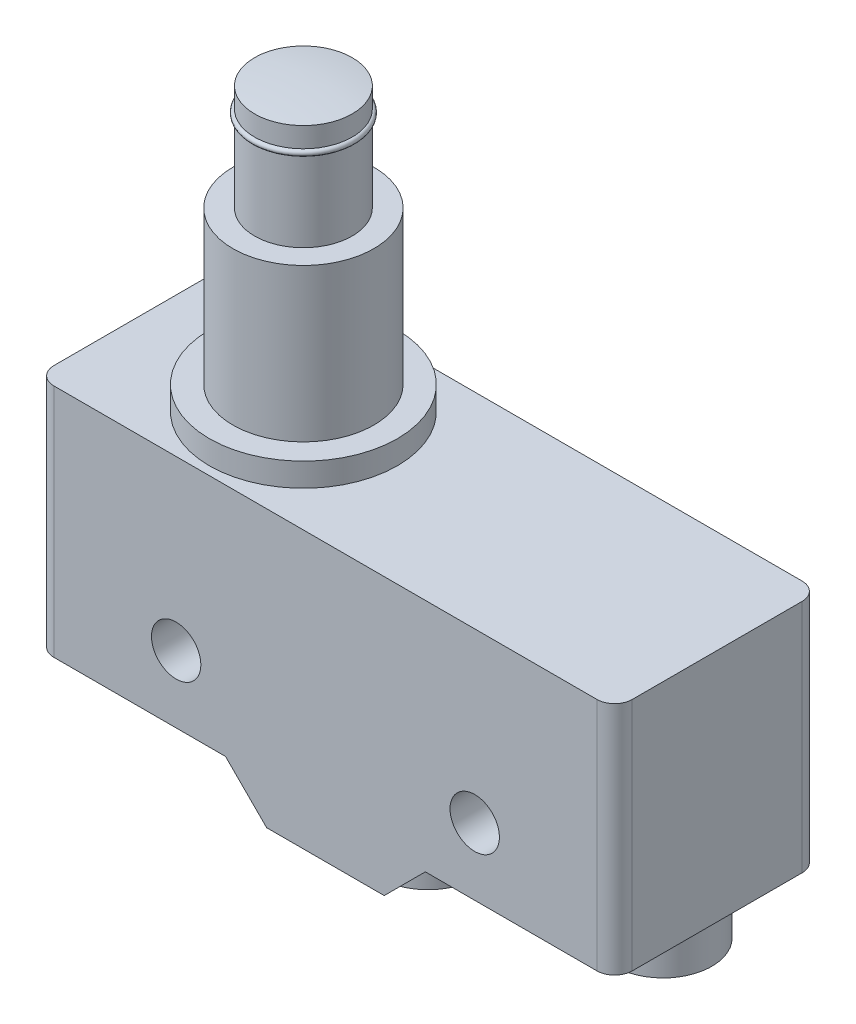
SolidWorks part; units mm, degrees
ref_plane "正面" through (0, 0, 0) normal (0, 0, 1) x (1, 0, 0)
ref_plane "平面" through (0, 0, 0) normal (0, 1, 0) x (1, 0, 0)
ref_plane "右側面" through (0, 0, 0) normal (1, 0, 0) x (0, 0, -1)
sketch "ｽｹｯﾁ1" plane through (0, 0, 0) normal (0, 0, 1) x (1, 0, 0)
  line L0 (0, 0) -> (31438.6503, 0) construction
  line L1 (0, 0) -> (0, -50000) construction
  line L2 (-5, -13.5) -> (5, -13.5)
  line L3 (24.6, 10) -> (-24.6, 10)
  line L4 (24.6, 10) -> (24.6, -10)
  line L5 (24.6, -10) -> (8.5, -10)
  line L6 (-24.6, 10) -> (-24.6, -10)
  line L7 (24.6, 10) -> (-24.6, -10) construction
  line L8 (24.6, -10) -> (-24.6, 10) construction
  line L9 (5, -13.5) -> (8.5, -10)
  line L10 (-5, -13.5) -> (-8.5, -10)
  line L11 (-8.5, -10) -> (-24.6, -10)
  line L12 (8.5, -10) -> (-8.5, -10) construction
  line L13 (-18.4698, -4.3) -> (49981.5302, -4.3) construction
  circle A0 centre (-12.7, -4.3) radius 2.1
  circle A1 centre (12.7, -4.3) radius 2.1
  point P5 (0, 0)
  point P12 (0, -13.5)
  dimension "D6" = 25.4
  dimension "D7" = 4.2
  dimension "D1" = 49.2
  dimension "D2" = 20
  dimension "D3" = 23.5
  dimension "D4" = 17
  dimension "D5" = 9.2
extrude "ﾎﾞｽ - 押し出し1" add sketch "ｽｹｯﾁ1" along normal blind 17.45
ref_plane "平面1" through (0, 0, 8.725) normal (0, 0, 1) x (1, 0, 0)
sketch "ｽｹｯﾁ2" plane through (0, -10, 0) normal (0, -1, 0) x (1, 0, 0)
  line L0 (24.6, 8.725) -> (-49975.4, 8.725) construction
  line L1 (24.6, 17.45) -> (24.6, 0) construction
  line L2 (0, 0) -> (0, -50000) construction
  circle A0 centre (-20, 8.725) radius 4.15
  circle A1 centre (20, 8.725) radius 4.15
  point P4 (24.6, 8.725)
  dimension "D1" = 20
  dimension "D2" = 8.3
extrude "ﾎﾞｽ - 押し出し2" add sketch "ｽｹｯﾁ2" along normal blind 3.5
sketch "ｽｹｯﾁ3" plane through (0, -13.5, 0) normal (0, -1, 0) x (1, 0, 0)
  line L0 (0, 0) -> (0, -50000) construction
  line L1 (-5, 0) -> (5, 0) construction
  line L2 (-5, 8.725) -> (49995, 8.725) construction
  line L3 (-5, 17.45) -> (-5, 0) construction
  circle A0 centre (0, 8.725) radius 4.15
  point P4 (0, 0)
  point P9 (-5, 8.725)
  dimension "D1" = 8.3
extrude "ﾎﾞｽ - 押し出し3" add sketch "ｽｹｯﾁ3" along normal blind 3.5
sketch "ｽｹｯﾁ4" plane through (0, 10, 0) normal (0, 1, 0) x (1, 0, 0)
  line L0 (0, 0) -> (0, -50000) construction
  line L1 (24.6, 0) -> (-24.6, 0) construction
  line L2 (-24.6, -8.725) -> (49975.4, -8.725) construction
  line L3 (-24.6, -17.45) -> (-24.6, 0) construction
  circle A0 centre (-10.6, -8.725) radius 8
  point P4 (0, 0)
  point P9 (-24.6, -8.725)
  dimension "D1" = 16
  dimension "D2" = 14
extrude "ﾎﾞｽ - 押し出し4" [suppressed] add sketch "ｽｹｯﾁ4" along normal blind 2
sketch "ｽｹｯﾁ5" plane through (0, 0, 8.725) normal (0, 0, 1) x (1, 0, 0)
  line L0 (-10.6, 27.1364) -> (-10.6, -49972.8636) construction
  line L1 (-24.6, 10) -> (-24.6, -10) construction
  line L2 (-10.6, 10) -> (-18.6, 10)
  line L3 (24.6, 10) -> (-24.6, 10) construction
  line L4 (-18.6, 10) -> (-18.6, 12)
  line L5 (-18.6, 12) -> (-16.6, 12)
  line L6 (-16.6, 12) -> (-16.6, 25)
  line L7 (-16.6, 25) -> (-14.75, 25)
  line L8 (-14.75, 25) -> (-14.75, 31.7884)
  line L9 (-14.75, 34) -> (-10.6, 34) construction
  line L10 (-10.6, 34) -> (-10.6, 10)
  line L11 (-10.6, 34) -> (-10.6, 34.2884)
  line L12 (-14.75, 32.2884) -> (-14.75, 34)
  line L13 (-14.75, 31.7884) -> (-14.75, 32.2884) construction
  arc A0 (-14.75, 34) -> (-10.6, 34.2884) centre (-10.6, 4.2884) cw
  arc A1 (-14.75, 32.2884) -> (-14.75, 31.7884) centre (-14.75, 32.0384) ccw
  dimension "D8" = 30
  dimension "D9" = 0.25
  dimension "D1" = 14
  dimension "D2" = 2
  dimension "D3" = 16
  dimension "D4" = 12
  dimension "D5" = 13
  dimension "D6" = 9
  dimension "D7" = 8.3
  dimension "D10" = 2
revolve "回転1" add sketch "ｽｹｯﾁ5" angle 360 about L0
fillet "ﾌｨﾚｯﾄ1" radius 1.5 4 edges at (-24.6, 0, 17.45) (-24.6, 0, 0) (24.6, 0, 0) (24.6, 0, 17.45)
